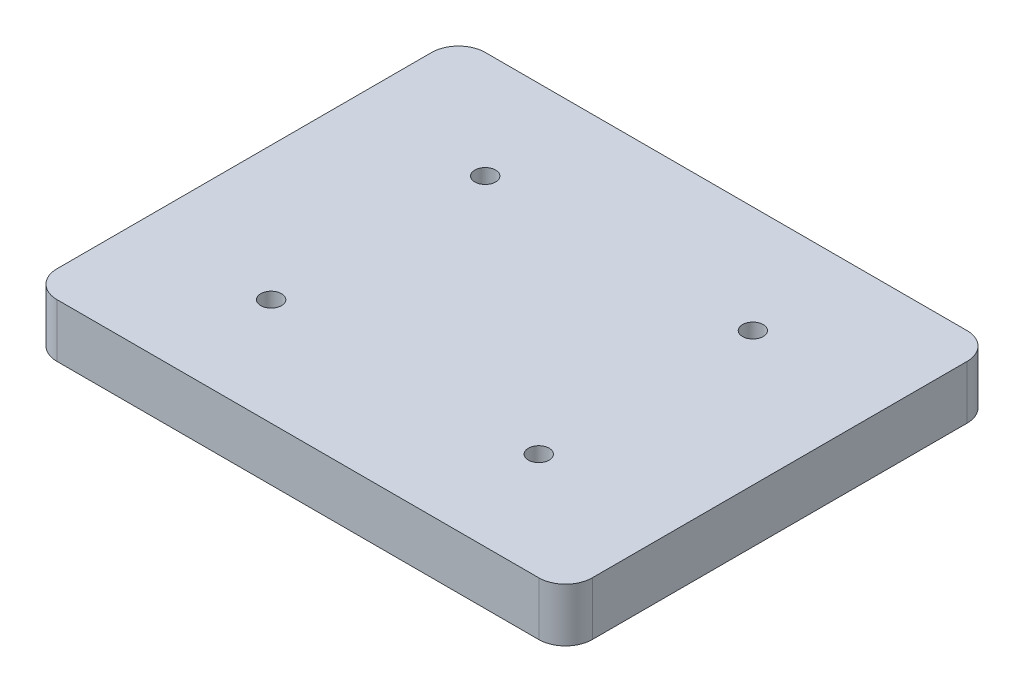
SolidWorks part; units mm, degrees
ref_plane "Front Plane" through (0, 0, 0) normal (0, 0, 1) x (1, 0, 0)
ref_plane "Top Plane" through (0, 0, 0) normal (0, 1, 0) x (1, 0, 0)
ref_plane "Right Plane" through (0, 0, 0) normal (1, 0, 0) x (0, 0, -1)
sketch "Sketch1" plane through (0, 0, 0) normal (0, 1, 0) x (1, 0, 0)
  line L1 (0, 0) -> (127, 0)
  line L2 (0, 0) -> (0, 101.6)
  line L3 (0, 101.6) -> (127, 101.6)
  line L4 (127, 0) -> (127, 101.6)
  dimension "D1" = 127
  dimension "D2" = 101.6
extrude "Boss-Extrude1" add sketch "Sketch1" along normal blind 12.7
sketch "Sketch2" plane through (0, 12.7, 0) normal (0, 1, 0) x (1, 0, 0)
  line L0 (0, 50.8) -> (127, 50.8) construction
  line L1 (0, 101.6) -> (0, 0) construction
  line L2 (127, 0) -> (127, 101.6) construction
  line L3 (63.5, 101.6) -> (63.5, 0) construction
  line L4 (127, 101.6) -> (0, 101.6) construction
  line L5 (0, 0) -> (127, 0) construction
  line L7 (31.75, 25.4) -> (95.25, 25.4) construction
  line L8 (31.75, 25.4) -> (31.75, 76.2) construction
  line L9 (31.75, 76.2) -> (95.25, 76.2) construction
  line L10 (95.25, 25.4) -> (95.25, 76.2) construction
  line L11 (31.75, 25.4) -> (95.25, 76.2) construction
  line L12 (31.75, 76.2) -> (95.25, 25.4) construction
  circle A0 centre (31.75, 76.2) radius 2.4638
  circle A1 centre (95.25, 76.2) radius 2.4638
  circle A2 centre (95.25, 25.4) radius 2.4638
  circle A3 centre (31.75, 25.4) radius 2.4638
  point P12 (63.5, 50.8)
  dimension "D5" = 4.9276
  dimension "D1" = 50.8
  dimension "D2" = 63.5
  dimension "D3" = 31.75
  dimension "D4" = 25.4
extrude "Cut-Extrude1" cut sketch "Sketch2" against normal through all both and the other way through all
fillet "Fillet1" radius 6.35 4 edges at (0, 6.35, 0) (127, 6.35, 0) (127, 6.35, -101.6) (0, 6.35, -101.6)
